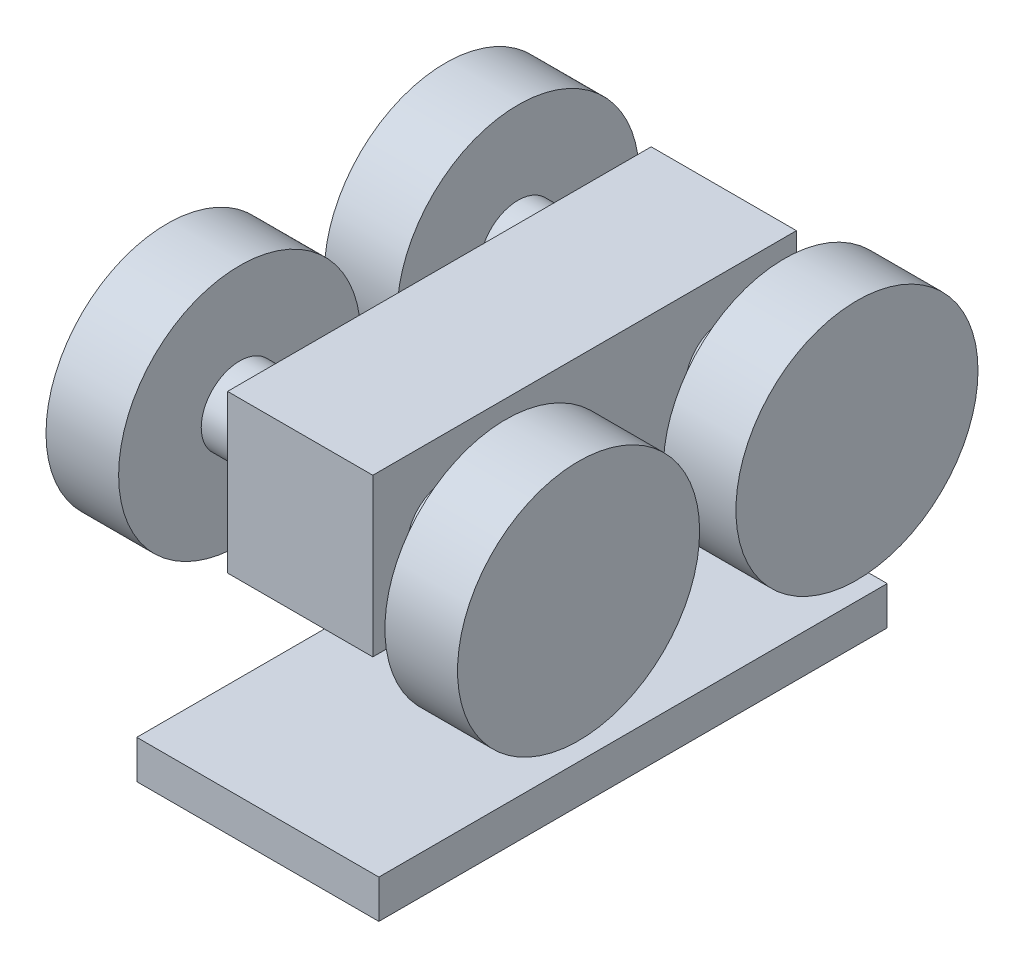
SolidWorks part; units mm, degrees
ref_plane "Alzado" through (0, 0, 0) normal (0, 0, 1) x (1, 0, 0)
ref_plane "Planta" through (0, 0, 0) normal (0, 1, 0) x (1, 0, 0)
ref_plane "Vista lateral" through (0, 0, 0) normal (1, 0, 0) x (0, 0, -1)
sketch "Croquis1" plane through (0, 0, 0) normal (0, 1, 0) x (1, 0, 0)
  line L1 (0, 0) -> (20, 0)
  line L2 (0, 0) -> (0, -42)
  line L3 (0, -42) -> (20, -42)
  line L4 (20, 0) -> (20, -42)
  dimension "D1" = 20
  dimension "D2" = 42
extrude "Saliente-Extruir1" add sketch "Croquis1" along normal blind 3.175
sketch "Croquis2" plane through (0, 3.175, 0) normal (0, 1, 0) x (1, 0, 0)
  line L0 (0, -21) -> (20, -21) construction
  line L1 (0, 0) -> (0, -42) construction
  line L2 (20, -42) -> (20, 0) construction
  circle A0 centre (10, -21) radius 3.175
  dimension "D1" = 6.35
extrude "Saliente-Extruir2" add sketch "Croquis2" along normal blind 12
sketch "Croquis3" plane through (0, 15.175, 0) normal (0, 1, 0) x (1, 0, 0)
  line L1 (4, -38.5) -> (16, -38.5)
  line L2 (4, -38.5) -> (4, -3.5)
  line L3 (4, -3.5) -> (16, -3.5)
  line L4 (16, -38.5) -> (16, -3.5)
  line L5 (4, -38.5) -> (16, -3.5) construction
  line L6 (4, -3.5) -> (16, -38.5) construction
  point P0 (10, -21)
  dimension "D1" = 12
  dimension "D2" = 35
extrude "Saliente-Extruir3" add sketch "Croquis3" along normal blind 13
sketch "Croquis4" plane through (4, 0, 0) normal (-1, 0, 0) x (0, 0, 1)
  line L0 (38.5, 21.675) -> (32.5, 21.675) construction
  line L1 (38.5, 28.175) -> (38.5, 15.175) construction
  line L2 (3.5, 21.675) -> (9.5, 21.675) construction
  line L3 (3.5, 28.175) -> (3.5, 15.175) construction
  circle A0 centre (9.5, 21.675) radius 3.175
  circle A1 centre (32.5, 21.675) radius 3.175
  dimension "D3" = 6.35
  dimension "D4" = 6.35
  dimension "D1" = 6
  dimension "D2" = 6
extrude "Saliente-Extruir4" add sketch "Croquis4" along normal blind 11
sketch "Croquis5" plane through (16, 0, 0) normal (1, 0, 0) x (0, 0, -1)
  circle A0 centre (-32.5, 21.675) radius 3.175
  circle A1 centre (-9.5, 21.675) radius 3.175
extrude "Saliente-Extruir5" add sketch "Croquis5" along normal blind 11
sketch "Croquis6" plane through (-7, 0, 0) normal (-1, 0, 0) x (0, 0, 1)
  circle A0 centre (9.5, 21.675) radius 10
  circle A1 centre (32.5, 21.675) radius 10
  circle A2 centre (9.5, 21.675) radius 3.175
  circle A3 centre (32.5, 21.675) radius 3.175
  dimension "D1" = 20
  dimension "D2" = 20
extrude "Saliente-Extruir6" add sketch "Croquis6" against normal blind 6
sketch "Croquis7" plane through (27, 0, 0) normal (1, 0, 0) x (0, 0, -1)
  circle A0 centre (-32.5, 21.675) radius 3.175
  circle A1 centre (-32.5, 21.675) radius 10
  circle A2 centre (-9.5, 21.675) radius 3.175
  circle A3 centre (-9.5, 21.675) radius 10
extrude "Saliente-Extruir7" add sketch "Croquis7" against normal blind 6
